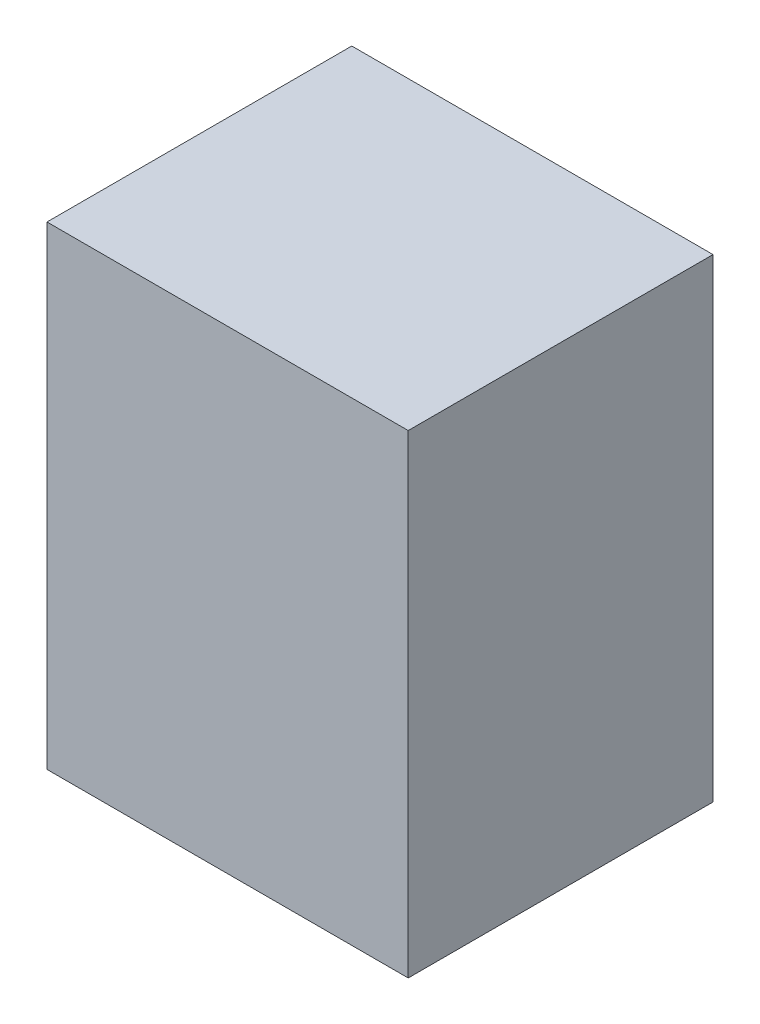
SolidWorks part; units mm, degrees
ref_plane "정면" through (0, 0, 0) normal (0, 0, 1) x (1, 0, 0)
ref_plane "윗면" through (0, 0, 0) normal (0, 1, 0) x (1, 0, 0)
ref_plane "우측면" through (0, 0, 0) normal (1, 0, 0) x (0, 0, -1)
sketch "Sketch1" plane through (0, 0, 0) normal (0, 0, 1) x (1, 0, 0)
  line L0 (-58, -45) -> (58, -45) construction
  line L1 (-34.1, -28.4) -> (-18.1, -28.4)
  line L2 (-34.1, -28.4) -> (-34.1, -49.4)
  line L3 (-34.1, -49.4) -> (-18.1, -49.4)
  line L4 (-18.1, -28.4) -> (-18.1, -49.4)
  line L5 (-34.1, -28.4) -> (-18.1, -49.4) construction
  line L6 (-34.1, -49.4) -> (-18.1, -28.4) construction
  line L7 (-58, 45) -> (-58, -45) construction
  point P0 (-26.1, -38.9)
  dimension "D1" = 16
  dimension "D2" = 21
  dimension "D3" = 4.4
  dimension "D4" = 23.9
extrude "Boss-Extrude1" add sketch "Sketch1" along normal blind 13.5
